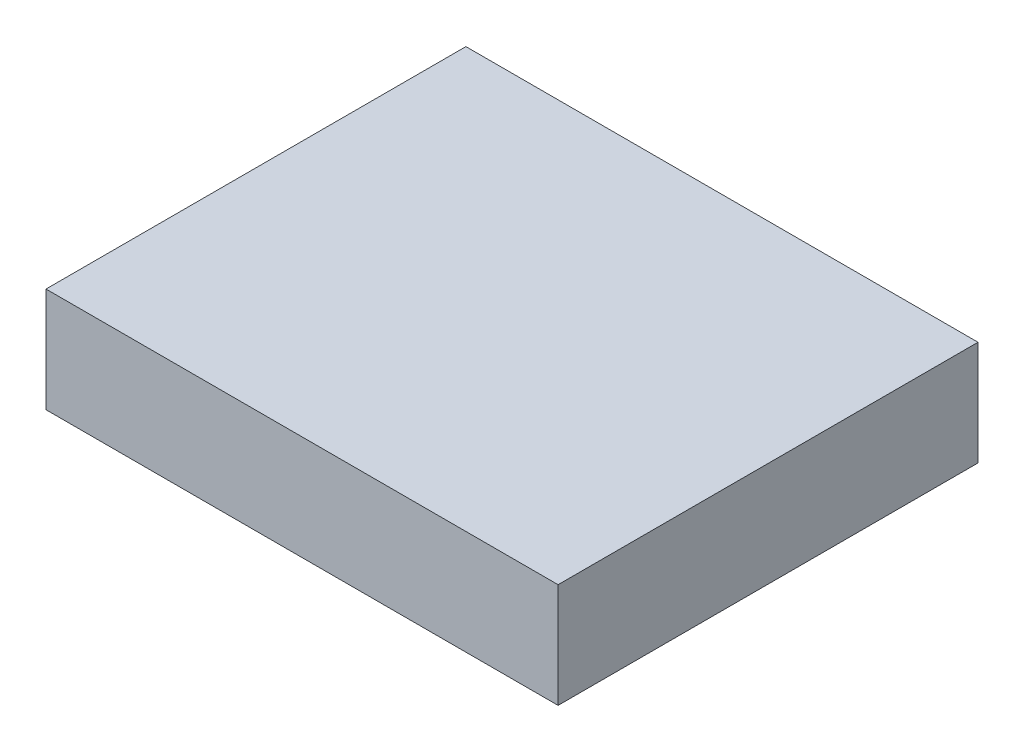
SolidWorks part; units mm, degrees
ref_plane "Front Plane" through (0, 0, 0) normal (0, 0, 1) x (1, 0, 0)
ref_plane "Top Plane" through (0, 0, 0) normal (0, 1, 0) x (1, 0, 0)
ref_plane "Right Plane" through (0, 0, 0) normal (1, 0, 0) x (0, 0, -1)
sketch "Sketch1" plane through (0, 0, 0) normal (0, 1, 0) x (1, 0, 0)
  line L1 (0, 0) -> (12, 0)
  line L2 (0, 0) -> (0, 9.84)
  line L3 (0, 9.84) -> (12, 9.84)
  line L4 (12, 0) -> (12, 9.84)
  dimension "D1" = 9.84
  dimension "D2" = 12
extrude "Boss-Extrude1" add sketch "Sketch1" along normal blind 2.45
